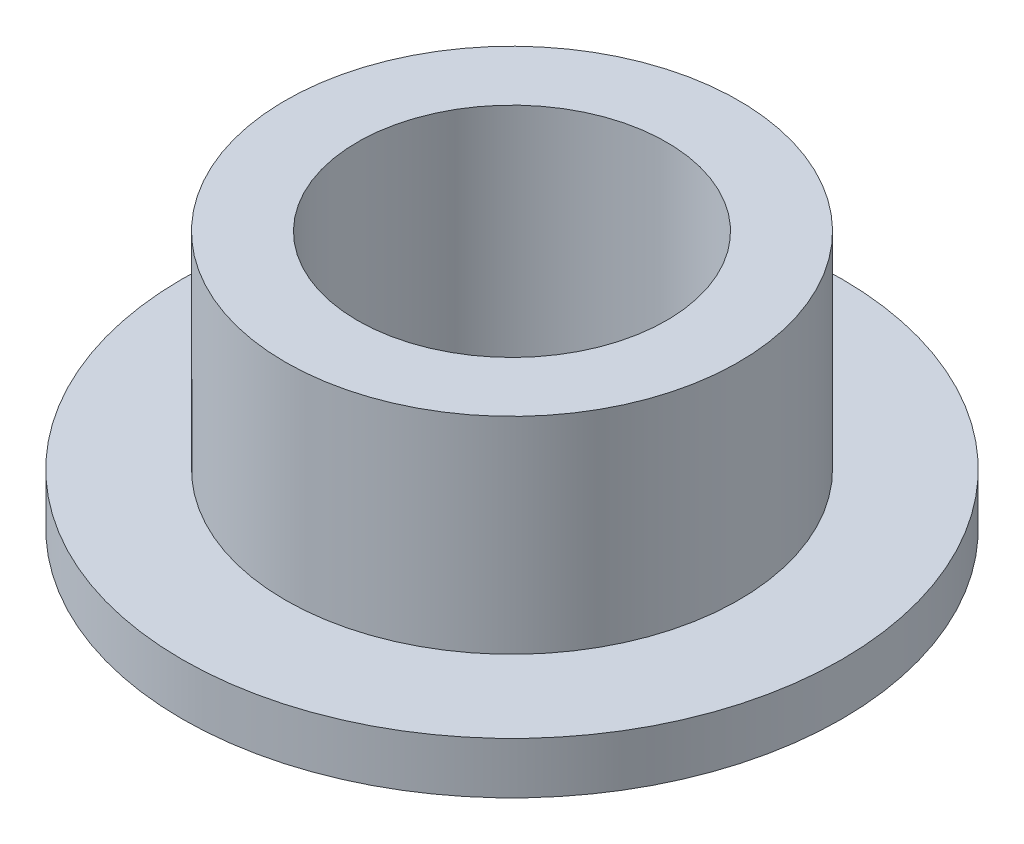
SolidWorks part; units mm, degrees
ref_plane "前基準面" through (0, 0, 0) normal (0, 0, 1) x (1, 0, 0)
ref_plane "上基準面" through (0, 0, 0) normal (0, 1, 0) x (1, 0, 0)
ref_plane "右基準面" through (0, 0, 0) normal (1, 0, 0) x (0, 0, -1)
sketch "草圖1" plane through (0, 0, 0) normal (0, 1, 0) x (1, 0, 0)
  circle A0 centre (0, 0) radius 16
  circle A1 centre (0, 0) radius 7.5
  dimension "D1" = 32
  dimension "D2" = 15
extrude "填料-伸長1" add sketch "草圖1" along normal blind 2.5
sketch "草圖2" plane through (0, 2.5, 0) normal (0, 1, 0) x (1, 0, 0)
  circle A0 centre (0, 0) radius 11
  circle A1 centre (0, 0) radius 7.5
  dimension "D1" = 22
  dimension "D2" = 15
extrude "填料-伸長2" add sketch "草圖2" along normal blind 10
